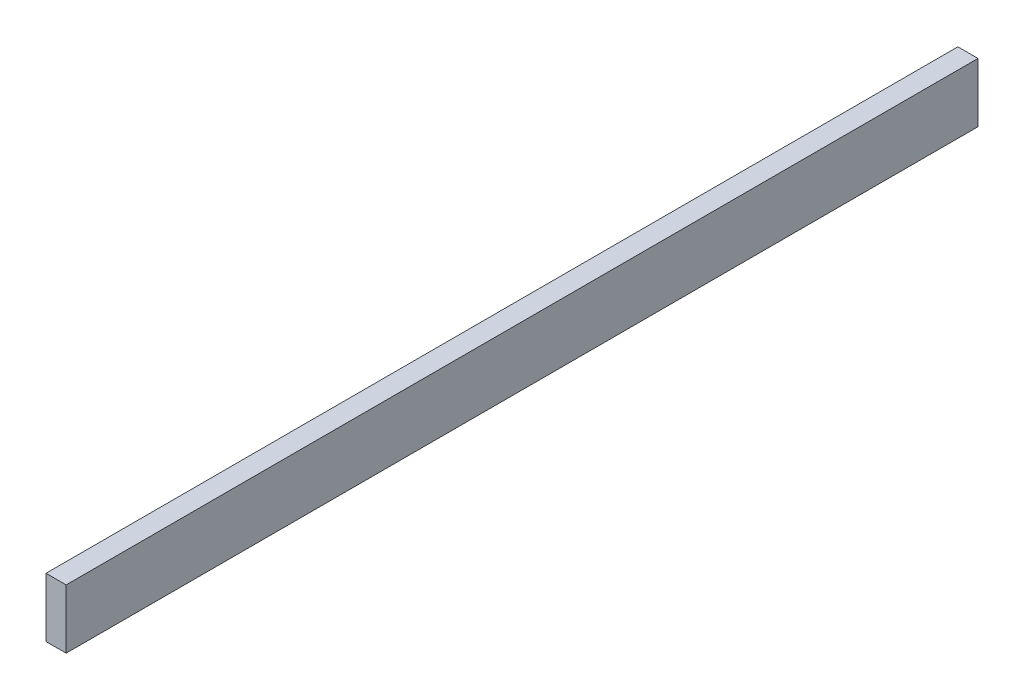
SolidWorks part; units mm, degrees
ref_plane "Front Plane" through (0, 0, 0) normal (0, 0, 1) x (1, 0, 0)
ref_plane "Top Plane" through (0, 0, 0) normal (0, 1, 0) x (1, 0, 0)
ref_plane "Right Plane" through (0, 0, 0) normal (1, 0, 0) x (0, 0, -1)
sketch "Sketch1" plane through (0, 0, 0) normal (0, 0, 1) x (1, 0, 0)
  line L1 (10.16, 29.845) -> (-10.16, 29.845)
  line L2 (10.16, 29.845) -> (10.16, -29.845)
  line L3 (10.16, -29.845) -> (-10.16, -29.845)
  line L4 (-10.16, 29.845) -> (-10.16, -29.845)
  line L5 (10.16, 29.845) -> (-10.16, -29.845) construction
  line L6 (10.16, -29.845) -> (-10.16, 29.845) construction
  point P0 (0, 0)
  dimension "D1" = 20.32
  dimension "D2" = 59.69
extrude "Boss-Extrude1" add sketch "Sketch1" along normal blind 920.118
